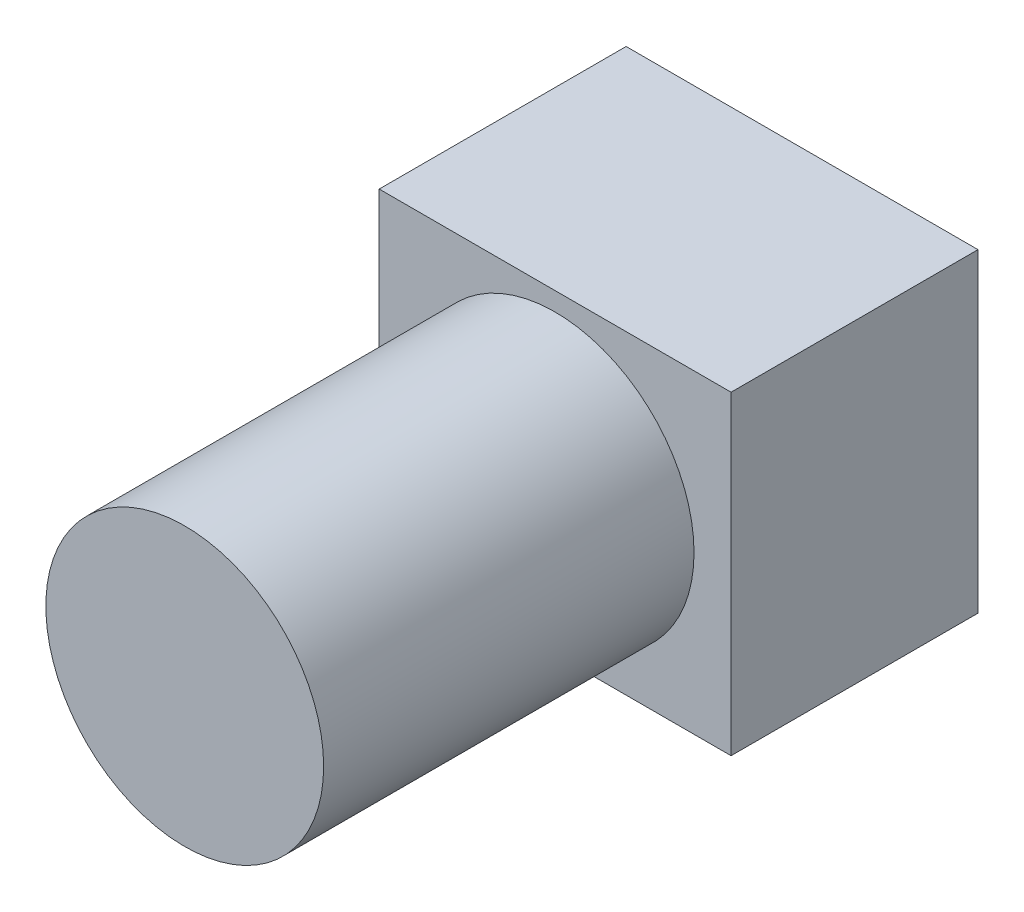
SolidWorks part; units mm, degrees
ref_plane "Piano frontale" through (0, 0, 0) normal (0, 0, 1) x (1, 0, 0)
ref_plane "Piano superiore" through (0, 0, 0) normal (0, 1, 0) x (1, 0, 0)
ref_plane "Piano destro" through (0, 0, 0) normal (1, 0, 0) x (0, 0, -1)
sketch "Schizzo1" plane through (0, 0, 126.0033) normal (0, 0, -1) x (-1, 0, 0)
  line L0 (4.2412, 38.794) -> (4.2412, 35.694) construction
  line L1 (-0.4588, 39.794) -> (5.2412, 39.794)
  line L2 (-0.4588, 39.794) -> (-0.4588, 34.694)
  line L3 (-0.4588, 34.694) -> (5.2412, 34.694)
  line L4 (5.2412, 39.794) -> (5.2412, 34.694)
  line L5 (0.5412, 38.794) -> (4.2412, 38.794) construction
  line L8 (0.5412, 35.694) -> (0.5412, 38.794) construction
  line L9 (4.2412, 35.694) -> (0.5412, 35.694) construction
  dimension "D1" = 1
  dimension "D2" = 1
  dimension "D3" = 1
  dimension "D4" = 1
extrude "Estrusione-Estrusione1" add sketch "Schizzo1" along normal blind 4
sketch "Schizzo2" plane through (0, 0, 122.0033) normal (0, 0, -1) x (-1, 0, 0)
  line L8 (-0.1088, 34.744) -> (4.8912, 34.744) construction
  line L9 (0.3912, 39.244) -> (4.3912, 39.244)
  line L10 (0.3912, 39.244) -> (0.3912, 35.244)
  line L11 (0.3912, 35.244) -> (4.3912, 35.244)
  line L12 (4.3912, 39.244) -> (4.3912, 35.244)
  line L13 (4.8912, 34.744) -> (4.8912, 39.744) construction
  line L14 (4.8912, 39.744) -> (-0.1088, 39.744) construction
  line L16 (0.5412, 35.694) -> (0.5412, 38.794) construction
  dimension "D1" = 0.5
  dimension "D2" = 0.5
  dimension "D3" = 0.5
  dimension "D4" = 0.15
extrude "Taglio-Estrusione1" cut sketch "Schizzo2" against normal blind 1
sketch "Schizzo3" plane through (0, 0, 126.0033) normal (0, 0, 1) x (1, 0, 0)
  circle A0 centre (-2.3912, 37.244) radius 2.25
  dimension "4.5" = 4.5
extrude "Estrusione-Estrusione2" add sketch "Schizzo3" along normal blind 6
